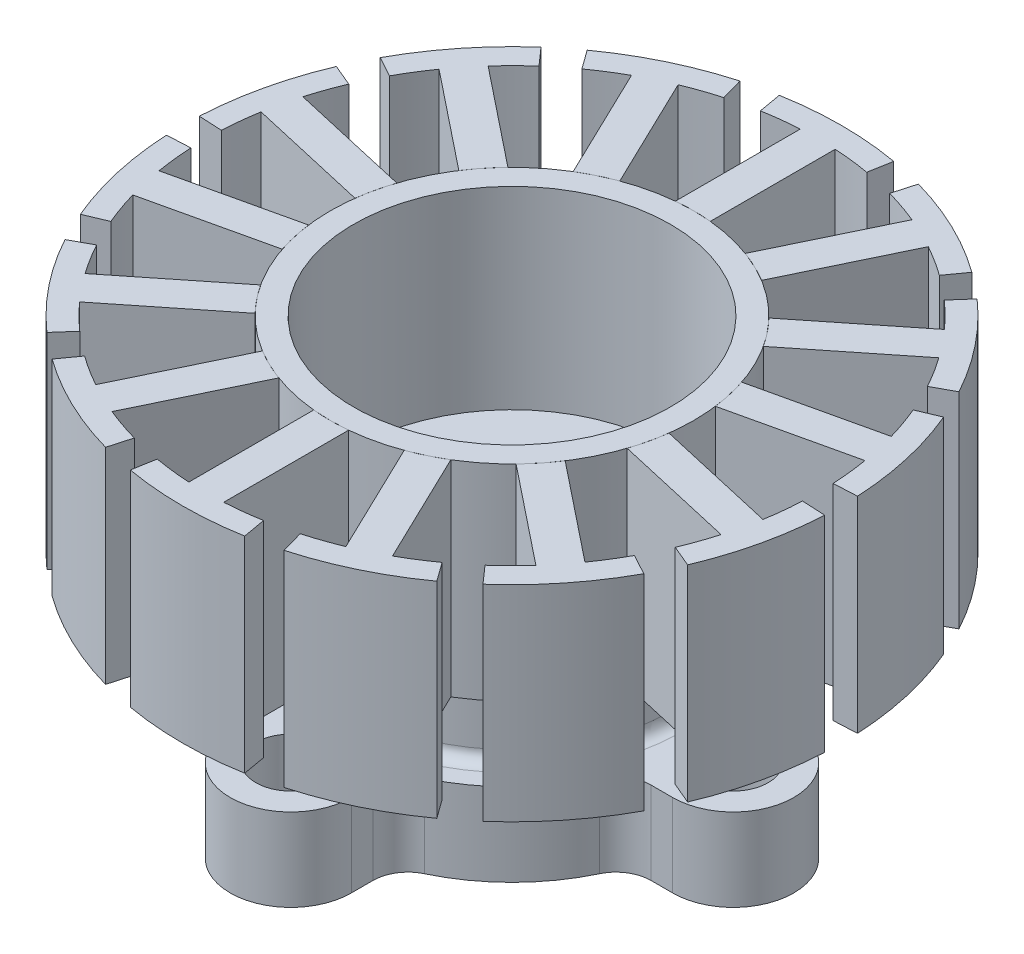
SolidWorks part; units mm, degrees
ref_plane "Front Plane" through (0, 0, 0) normal (0, 0, 1) x (1, 0, 0)
ref_plane "Top Plane" through (0, 0, 0) normal (0, 1, 0) x (1, 0, 0)
ref_plane "Right Plane" through (0, 0, 0) normal (1, 0, 0) x (0, 0, -1)
sketch "Эскиз1" plane through (0, 0, 0) normal (0, 1, 0) x (1, 0, 0)
  line L0 (-2.6, 9.5) -> (-2.6, 7.5657)
  line L1 (2.6, 9.5) -> (2.6, 7.5657)
  line L3 (-9.5, 2.6) -> (-7.5657, 2.6)
  line L15 (-9.5, -2.6) -> (-7.5657, -2.6)
  line L16 (9.5, 2.6) -> (7.5657, 2.6)
  line L17 (9.5, -2.6) -> (7.5657, -2.6)
  line L18 (-2.6, -9.5) -> (-2.6, -7.5657)
  line L19 (2.6, -9.5) -> (2.6, -7.5657)
  circle A14 centre (0, 0) radius 9.5 construction
  circle A15 centre (0, 9.5) radius 1.5
  circle A16 centre (9.5, 0) radius 1.5
  circle A17 centre (-9.5, 0) radius 1.5
  circle A18 centre (0, -9.5) radius 1.5
  arc A19 (2.6, 9.5) -> (-2.6, 9.5) centre (0, 9.5) ccw
  arc A20 (9.5, -2.6) -> (9.5, 2.6) centre (9.5, 0) ccw
  arc A21 (-9.5, 2.6) -> (-9.5, -2.6) centre (-9.5, 0) ccw
  arc A22 (-2.6, -9.5) -> (2.6, -9.5) centre (0, -9.5) ccw
  circle A23 centre (0, 0) radius 6.25
  arc A24 (-2.6, 7.5657) -> (-7.5657, 2.6) centre (0, 0) ccw
  arc A25 (-7.5657, -2.6) -> (-2.6, -7.5657) centre (0, 0) ccw
  arc A26 (7.5657, 2.6) -> (2.6, 7.5657) centre (0, 0) ccw
  arc A27 (2.6, -7.5657) -> (7.5657, -2.6) centre (0, 0) ccw
  dimension "D1" = 19
  dimension "D2" = 3
  dimension "D3" = 5.2
  dimension "D4" = 12.5
  dimension "D5" = 16
extrude "Бобышка-Вытянуть1" add sketch "Эскиз1" along normal blind 3.55
fillet "Скругление1" radius 1.5 8 edges at (-7.5657, 1.775, -2.6) (-2.6, 1.775, -7.5657) (2.6, 1.775, -7.5657) (7.5657, 1.775, -2.6) (7.5657, 1.775, 2.6) (2.6, 1.775, 7.5657) (-2.6, 1.775, 7.5657) (-7.5657, 1.775, 2.6)
sketch "Эскиз2" plane through (0, 0, 0) normal (0, 0, 1) x (1, 0, 0)
  line L0 (0, 0) -> (0, 7.15) construction
  line L1 (-4.75, 3.55) -> (-6.75, 3.55)
  line L3 (-6.75, 3.55) -> (-6.75, 7.15)
  line L4 (1.5, 3.55) -> (-1.5, 3.55) construction
  line L5 (-6.75, 7.15) -> (-4.75, 7.15)
  line L6 (-4.75, 7.15) -> (-4.75, 3.55)
  dimension "D1" = 3.6
  dimension "D2" = 2
  dimension "D3" = 13.5
revolve "Повернуть1" add sketch "Эскиз2" angle 360 about L0
fillet "Скругление2" radius 0.5 1 edges at (0, 3.55, -6.75)
sketch "Эскиз4" plane through (0, 0, 0) normal (0, 0, 1) x (1, 0, 0)
  line L1 (-7.8017, 15.42) -> (-6.8017, 15.42)
  line L2 (-6.8017, 15.42) -> (-6.8017, 6.6)
  line L4 (0, 0) -> (0, 15.42) construction
  line L6 (-7.8017, 15.42) -> (-7.8017, 6.6)
  line L7 (-7.8017, 6.6) -> (-6.8017, 6.6)
  point P2 (0, 0)
  point P6 (0, 0)
  point P9 (0, 0)
  dimension "D1" = 1
  dimension "D2" = 6.6
  dimension "D3" = 8.82
  dimension "D4" = 6.8017
revolve "Повернуть2" add sketch "Эскиз4" angle 360 about L4
sketch "Эскиз5" plane through (0, 15.42, 0) normal (0, 1, 0) x (1, 0, 0)
  line L0 (0, 0) -> (0, 14.15) construction
  line L1 (0.75, 13.1286) -> (0.75, 7.7656)
  line L6 (-0.75, 13.1286) -> (-0.75, 7.7656)
  line L7 (0, 0) -> (-2.4571, 13.935) construction
  line L8 (0, 0) -> (2.4571, 13.935) construction
  line L9 (-2.4571, 13.935) -> (-2.2835, 12.9502)
  line L10 (2.4571, 13.935) -> (2.2835, 12.9502)
  circle A2 centre (0, 0) radius 16.95 construction
  arc A8 (2.4571, 13.935) -> (-2.4571, 13.935) centre (0, 0) ccw
  circle A9 centre (0, 0) radius 7.8017 construction
  arc A10 (0.75, 7.7656) -> (-0.75, 7.7656) centre (0, 0) ccw
  arc A11 (2.2835, 12.9502) -> (0.75, 13.1286) centre (0, 0) ccw
  arc A12 (-0.75, 13.1286) -> (-2.2835, 12.9502) centre (0, 0) ccw
  dimension "D2" = 2.8
  dimension "D1" = 33.9
  dimension "D3" = 1
  dimension "D4" = 20
  dimension "D5" = 1.5
extrude "Бобышка-Вытянуть2" add sketch "Эскиз5" against normal up to surface (8.82 mm away) separate body up to face at (0, 6.6, -6.8017)
pattern_circular "Круговой массив1" count 14 over 360 about axis through (0, 0, 0) along (0, 1, 0) of bodies 104
